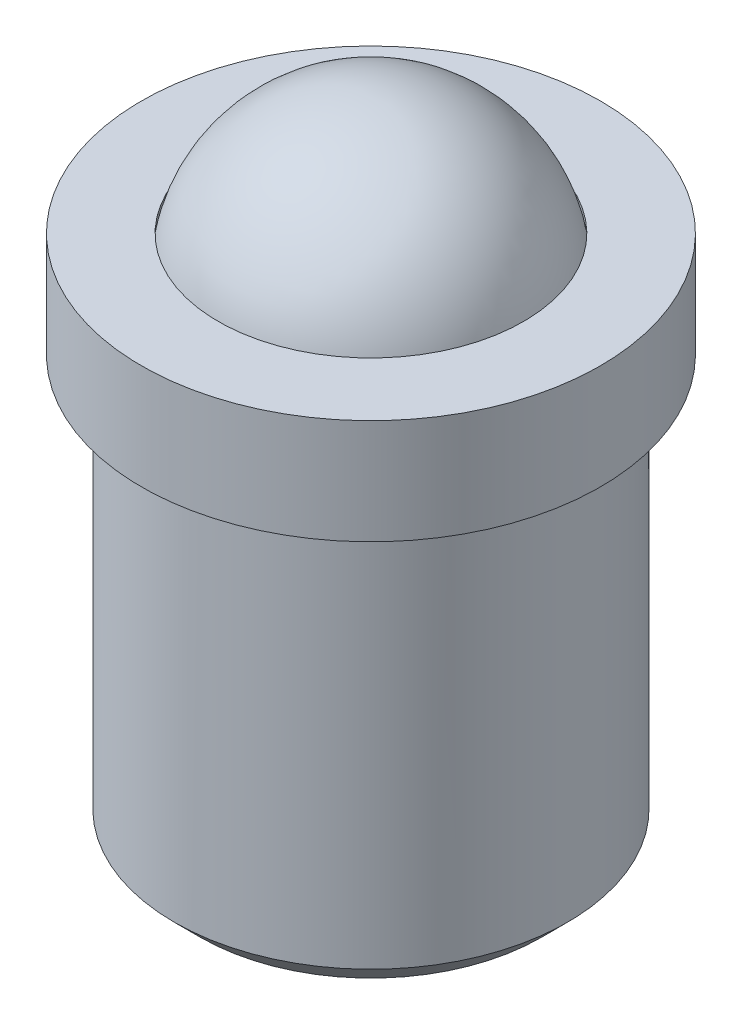
SolidWorks part; units mm, degrees
ref_plane "Front" through (0, 0, 0) normal (0, 0, 1) x (1, 0, 0)
ref_plane "Top" through (0, 0, 0) normal (0, 1, 0) x (1, 0, 0)
ref_plane "Right" through (0, 0, 0) normal (1, 0, 0) x (0, 0, -1)
sketch "草图1" plane through (0, 0, 0) normal (1, 0, 0) x (0, 0, -1)
  line L0 (0.3, 0) -> (1.5, 0)
  line L1 (1.5, 0) -> (1.5, 3.2)
  line L2 (1.5, 3.2) -> (1.75, 3.2)
  line L3 (1.75, 3.2) -> (1.75, 4)
  line L4 (1.75, 4) -> (1.1644, 4)
  line L6 (1.2, 0.3) -> (0.3, 0.3)
  line L8 (0, 0) -> (0, 5.4955) construction
  line L11 (0, 4.9) -> (-0.7192, 5.5273) construction
  line L19 (1.2, 3.71) -> (1.2, 0.3)
  line L20 (1.2, 0.29) -> (0.01, 0.29) construction
  line L21 (1.19, 0.3) -> (0, 0.3) construction
  line L22 (0.3, 0.3) -> (0.3, 0)
  line L23 (1.2, 3.71) -> (1.2, 0.29) construction
  line L24 (1.19, 3.71) -> (1.19, 0.3) construction
  line L25 (0.01, 0.01) -> (1.49, 0.01) construction
  line L26 (0.01, 0.29) -> (0.01, 0.01) construction
  line L27 (1.49, 0.01) -> (1.49, 3.21) construction
  line L28 (1.49, 3.21) -> (1.74, 3.21) construction
  line L29 (1.74, 3.21) -> (1.74, 3.99) construction
  line L30 (1.74, 3.99) -> (1.1669, 3.99) construction
  line L31 (1.75, 4) -> (1.1541, 4) construction
  line L33 (0, 0) -> (1.5, 0) construction
  line L34 (0, 0.3) -> (0, 0) construction
  arc A0 (0, 2.52) -> (0, 4.9) centre (0, 3.71) ccw construction
  arc A1 (1.2, 3.71) -> (1.1644, 4) centre (0, 3.71) ccw
  arc A2 (1.2, 3.71) -> (1.1669, 3.99) centre (0, 3.71) ccw construction
  arc A3 (1.19, 3.71) -> (1.1541, 4) centre (0, 3.71) ccw construction
  dimension "D6" = 2.38
  dimension "D1" = 1.5
  dimension "D2" = 4
  dimension "D3" = 0.8
  dimension "D4" = 0.9
  dimension "D5" = 1.75
  dimension "D7" = 0.01
  dimension "D8" = 0.3
  dimension "D9" = 0.3
  dimension "D10" = 0.3
revolve "旋转1" add sketch "草图1" angle 360 about L8
chamfer "倒角1" distance 0.2 angle 45 1 edges at (0, 0, -1.5)
sketch "草图2" plane through (0, 0, 0) normal (1, 0, 0) x (0, 0, -1)
  line L0 (1.2, 3.71) -> (-1.2, 3.71) construction
  line L1 (0, 4.9) -> (0, 2.52)
  line L2 (0, 5.5329) -> (0, 0) construction
  arc A0 (0, 2.52) -> (0, 4.9) centre (0, 3.71) ccw
  dimension "D1" = 2.38
revolve "旋转2" add sketch "草图2" angle 360 about L2
